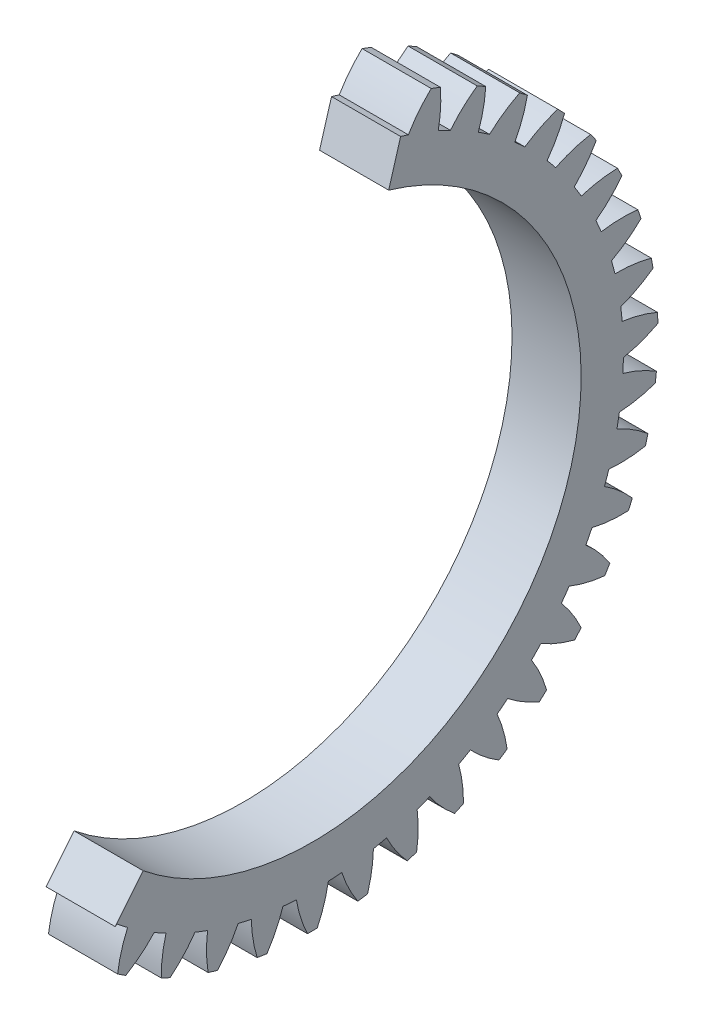
SolidWorks part; units mm, degrees
ref_plane "Plane1" through (0, 0, 0) normal (0, 0, 1) x (1, 0, 0)
ref_plane "Plane2" through (0, 0, 0) normal (0, 1, 0) x (1, 0, 0)
ref_plane "Plane3" through (0, 0, 0) normal (1, 0, 0) x (0, 0, -1)
sketch "HoldingSke" plane through (0, 0, 0) normal (0, 1, 0) x (1, 0, 0)
  line L0 (0, 0) -> (0.3657, -0.341)
  line L1 (-15, 0) -> (100, 0) construction
  line L2 (0, 0) -> (-2.1039, 2.3779)
  line L3 (0, 0) -> (-11.863, 4.5341)
  line L4 (0, 0) -> (6.316, 5.8897)
  line L5 (0, 0) -> (-46.8476, -17.4728)
  line L6 (0, 0) -> (-7.4607, -5.0337)
  line L7 (-2.1039, 2.3779) -> (8.6586, 51.2059)
  line L8 (-76.2, 54.61) -> (-75.2, 54.61)
  line L9 (-71.009, 38.7566) -> (-53.1078, 45.2721)
  line L10 (-76.2, 71.12) -> (104.1128, 71.12)
  line L11 (0, 0) -> (-9, 0)
  line L12 (-76.2, 101.6) -> (-76.133, 101.6)
  line L13 (24.9733, 27.94) -> (52.9518, 28.4284)
  line L14 (24.9733, 27.94) -> (24.9743, 27.94)
  line L15 (24.9733, 27.94) -> (100.4006, 29.5858)
  line L16 (-63.627, -2) -> (-12.827, -2)
  circle A0 centre (0, 0) radius 3
  circle A1 centre (0, 0) radius 37.5
  circle A2 centre (0, 0) radius 37.5
  circle A3 centre (0, 0) radius 3
  dimension "MHD" = 75
  dimension "Hub_dia" = 75
  dimension "Bore" = 6
  dimension "MBD" = 6
  dimension "Num_teeth" = 43
  dimension "Pitch" = 0.5
  dimension "Overall_len" = 50
  dimension "Show_teeth" = 43
  dimension "Thickness" = 9
  dimension "OAL" = 50.0001
  dimension "T_dim" = 1
  dimension "Ap" = 20
  dimension "H" = 19.05
  dimension "Pitch_radius" = 180.3128
  dimension "Width" = 9
  dimension "Backlash" = 0.067
  dimension "Addendum_fac" = 1
  dimension "Dedendum_fac" = 1.25
  dimension "Clearance_fac" = 0.25
  dimension "Dedendum_add" = 0.001
  dimension "Module" = 2
sketch "BasProSke" plane through (0, 0, 0) normal (0, 1, 0) x (1, 0, 0)
  line L0 (-10, 0) -> (60, 0) construction
  line L1 (0, 0) -> (0, 45)
  line L2 (0, 0) -> (9, 0)
  line L3 (9, 0) -> (9, 45)
  line L4 (9, 45) -> (0, 45)
  dimension "Thickness" = 9
  dimension "Diameter" = 90
revolve "Base-Revolve" add sketch "BasProSke" angle 360 about L0
sketch "TooCutSke" plane through (0, 0, 0) normal (1, 0, 0) x (0, 0, -1)
  line L1 (0, 0) -> (0, 107) construction
  line L2 (0, 0) -> (-1.6877, 42.9669) construction
  line L3 (0, 0) -> (-6.274, 85.7216) construction
  line L4 (-1.6877, 42.9669) -> (-3.137, 42.8608) construction
  arc A0 (0.8751, 40.4895) -> (-0.8751, 40.4895) centre (0, 0) ccw
  arc A1 (2.6611, 44.9467) -> (-2.6611, 44.9467) centre (0, 0) ccw
  circle A2 centre (0, 0) radius 43 construction
  circle A3 centre (0, 0) radius 40.4068 construction
  arc A4 (-0.8751, 40.4895) -> (-2.6611, 44.9467) centre (-17.5777, 36.3831) ccw
  arc A5 (2.6611, 44.9467) -> (0.8751, 40.4895) centre (17.5777, 36.3831) ccw
  dimension "Root_dia" = 80.998
  dimension "Overcut_dia" = 90.0508
  dimension "Pitch_dia" = 86
  dimension "Base_dia" = 80.8136
  dimension "Flank_rad" = 17.2
  dimension "Half_ang" = 4.186
  dimension "Half_CT" = 1.4532
extrude "ToothCut" cut sketch "TooCutSke" along normal through all
fillet "Breaks" [suppressed] radius 0.04
fillet "RootFillets" [suppressed] radius 0.501
pattern_circular "TeethCuts" count 43 every 8.372 about axis through (-10, 0, 0) along (1, 0, 0) of "ToothCut", "RootFillets", "Breaks"
sketch "HubNeaOneSke" plane through (0, 0, 0) normal (-1, 0, 0) x (0, 0, 1)
  circle A0 centre (0, 0) radius 37.5
  dimension "Diameter" = 75
extrude "HubNearOne" [suppressed] add sketch "HubNeaOneSke" along normal blind 41.0001
sketch "HubNeaBotSke" plane through (0, 0, 0) normal (-1, 0, 0) x (0, 0, 1)
  circle A0 centre (0, 0) radius 37.5
  dimension "Diameter" = 75
extrude "HubNearBoth" [suppressed] add sketch "HubNeaBotSke" along normal blind 20.5
ref_plane "FarPln" through (9, 0, 0) normal (1, 0, 0) x (0, 0, -1)
sketch "HubFarSke" plane through (9, 0, 0) normal (1, 0, 0) x (0, 0, -1)
  circle A0 centre (0, 0) radius 37.5
  dimension "Diameter" = 75
extrude "HubFar" [suppressed] add sketch "HubFarSke" along normal blind 20.5
sketch "BorSke" plane through (0, 0, 0) normal (1, 0, 0) x (0, 0, -1)
  circle A0 centre (0, 0) radius 3
  dimension "Diameter" = 6
extrude "Bore" cut sketch "BorSke" along normal mid plane 100.0001
sketch "KeySke" plane through (0, 0, 0) normal (1, 0, 0) x (0, 0, -1)
  line L0 (-1, 0) -> (-1, 4)
  line L1 (-1, 4) -> (1, 4)
  line L2 (1, 4) -> (1, 0)
  line L3 (0, 0) -> (0, 34) construction
  line L4 (-1, 0) -> (1, 0)
  dimension "Offset" = 4
  dimension "Width" = 2
extrude "Keyway" [suppressed] cut sketch "KeySke" along normal mid plane 100.0001
pattern_circular "Keyway2" [suppressed] count 2 every 90 about axis through (-10, 0, 0) along (1, 0, 0)
sketch "Szkic1" plane through (0, 0, 0) normal (1, 0, 0) x (0, 0, -1)
  line L1 (0, 0) -> (-31.4677, -38.8559) construction
  line L3 (14.1945, 47.9429) -> (0, 0) construction
  line L4 (-31.4677, -38.8559) -> (-22.0274, -27.1991)
  line L5 (14.1945, 47.9429) -> (9.9361, 33.56)
  line L6 (9.9361, 33.56) -> (14.1945, 47.9429)
  line L7 (-22.0274, -27.1991) -> (-31.4677, -38.8559)
  arc A0 (-31.4677, -38.8559) -> (14.1945, 47.9429) centre (0, 0) cw
  circle A1 centre (0, 0) radius 35 construction
  arc A3 (9.9361, 33.56) -> (-22.0274, -27.1991) centre (0, 0) cw
  arc A5 (-22.0274, -27.1991) -> (9.9361, 33.56) centre (0, 0) ccw
  dimension "D2" = 50
  dimension "D3" = 70
  dimension "D1" = 157.49
sketch "Szkic2" plane through (0, 0, 0) normal (1, 0, 0) x (0, 0, -1)
  line L0 (-31.4677, -38.8559) -> (-22.0274, -27.1991) construction
  line L1 (14.1945, 47.9429) -> (9.9361, 33.56) construction
  line L2 (-31.4677, -38.8559) -> (-22.0274, -27.1991)
  line L3 (14.1945, 47.9429) -> (9.9361, 33.56)
  arc A0 (-22.0274, -27.1991) -> (9.9361, 33.56) centre (0, 0) ccw construction
  arc A1 (14.1945, 47.9429) -> (-31.4677, -38.8559) centre (0, 0) ccw construction
  arc A2 (-22.0274, -27.1991) -> (9.9361, 33.56) centre (0, 0) ccw
  arc A3 (14.1945, 47.9429) -> (-31.4677, -38.8559) centre (0, 0) ccw
extrude "Wytnij-wyciągnięcie1" cut sketch "Szkic2" along normal through all
equation "' \"Module@HoldingSke\" = 6.35"
equation "' \"Num_teeth@HoldingSke\" = 12"
equation "' \"Ap@HoldingSke\" =  20"
equation "' \"Ap@HoldingSke\" = 20"
equation "' \"Width@HoldingSke\" = 0.5 * 25.4"
equation "' \"Hub_dia@HoldingSke\"= 1 * 25.4"
equation "' \"Hub_dia@HoldingSke\" = 1 * 25.4"
equation "' \"Overall_len@HoldingSke\" = 1.0 * 25.4"
equation "' \"Bore@HoldingSke\" = 0.75 * 25.4"
equation "' \"T_dim@HoldingSke\" = 0.1 * 25.4"
equation "' \"Width@KeySke\" = 0.25 * 25.4"
equation "' \"Show_teeth@HoldingSke\" = 13"
equation "' \"Backlash@HoldingSke\" = 0.009 * 25.4"
equation "' \"Addendum_fac@HoldingSke\" = 1.0"
equation "' \"Dedendum_fac@HoldingSke\" = 1.25"
equation "' \"Dedendum_add@HoldingSke\" = 0.00005 * 25.4"
equation "' \"Clearance_fac@HoldingSke\" = 0.25"
equation "\"Pitch@HoldingSke\" = 1 / \"Module@HoldingSke\""
equation "\"Overcut_dia@TooCutSke\" = (\"Num_teeth@HoldingSke\" + 2 * \"Addendum_fac@HoldingSke\") / \"Pitch@HoldingSke\" + 0.002 * 25.4"
equation "\"Pitch_dia@TooCutSke\" = \"Num_teeth@HoldingSke\" / \"Pitch@HoldingSke\""
equation "\"Base_dia@TooCutSke\" = \"Num_teeth@HoldingSke\" / \"Pitch@HoldingSke\" * cos((\"Ap@HoldingSke\"  * 3.14159265 / 180))"
equation "\"Root_dia@TooCutSke\" = (\"Num_teeth@HoldingSke\" + 2) / \"Pitch@HoldingSke\" - 2 * (\"Addendum_fac@HoldingSke\" + \"Dedendum_fac@HoldingSke\") / \"Pitch@HoldingSke\" - \"Dedendum_add@HoldingSke\" * 2"
equation "\"Half_ang@TooCutSke\" = 180 / \"Num_teeth@HoldingSke\""
equation "\"Half_CT@TooCutSke\" = \"Num_teeth@HoldingSke\" / \"Pitch@HoldingSke\" * sin((3.14159265 / 2 / \"Num_teeth@HoldingSke\")) / 2 - 7 * \"Backlash@HoldingSke\" / 4"
equation "\"Flank_rad@TooCutSke\" = \"Num_teeth@HoldingSke\" / \"Pitch@HoldingSke\" / 5"
equation "\"Radius@RootFillets\" = \"Clearance_fac@HoldingSke\" / \"Pitch@HoldingSke\" + \"Dedendum_add@HoldingSke\""
equation "\"Break_rad@Breaks\" = 0.02 / \"Pitch@HoldingSke\""
equation "\"Thickness@HoldingSke\" = \"Width@HoldingSke\""
equation "\"OAL@HoldingSke\" = \"Thickness@HoldingSke\""
equation "\"MHD@HoldingSke\" = (\"Num_teeth@HoldingSke\" + 2) / \"Pitch@HoldingSke\" - 2 * (\"Addendum_fac@HoldingSke\" + \"Dedendum_fac@HoldingSke\")  / \"Pitch@HoldingSke\" - \"Dedendum_add@HoldingSke\" * 2"
equation "\"MBD@HoldingSke\" = (\"Num_teeth@HoldingSke\" + 2) / \"Pitch@HoldingSke\" - 2 * (\"Addendum_fac@HoldingSke\" + \"Dedendum_fac@HoldingSke\")  / \"Pitch@HoldingSke\" - \"Dedendum_add@HoldingSke\" * 2 - 0.002 * 25.4"
equation "\"MHD@HoldingSke\" = ((sgn( \"MHD@HoldingSke\" - \"Hub_dia@HoldingSke\" )-1)*( \"MHD@HoldingSke\" - \"Hub_dia@HoldingSke\" ))/-2+ \"Hub_dia@HoldingSke\""
equation "\"MBD@HoldingSke\" = ((sgn( \"MBD@HoldingSke\" - \"Bore@HoldingSke\" )-1)*( \"MBD@HoldingSke\" - \"Bore@HoldingSke\" ))/-2+ \"Bore@HoldingSke\""
equation "\"OAL@HoldingSke\" = ((sgn( \"OAL@HoldingSke\" - \"Overall_len@HoldingSke\" )+1)*( \"OAL@HoldingSke\" - \"Overall_len@HoldingSke\" ))/2 + \"Overall_len@HoldingSke\" + 0.000002 * 25.4"
equation "\"Num_teeth@TeethCuts\" = int( \"Show_teeth@HoldingSke\" ) + 1"
equation "\"Num_teeth@TeethCuts\" = ((sgn( \"Num_teeth@TeethCuts\" - \"Num_teeth@HoldingSke\" )-1)*( \"Num_teeth@TeethCuts\" - \"Num_teeth@HoldingSke\" ))/-2+ \"Num_teeth@HoldingSke\""
equation "\"Num_teeth@TeethCuts\" = ((sgn( \"Num_teeth@TeethCuts\" - 2.0)+1)*( \"Num_teeth@TeethCuts\" - 2.0))/2 +2.0"
equation "\"Angle@TeethCuts\" = 360.0 / \"Num_teeth@HoldingSke\""
equation "\"Diameter@BasProSke\" = (\"Num_teeth@HoldingSke\" + 2 * \"Addendum_fac@HoldingSke\") / \"Pitch@HoldingSke\""
equation "\"Thickness@BasProSke\"  = \"Thickness@HoldingSke\""
equation "' \"Fillet_rad@BasProSke\" =  \"Thickness@HoldingSke\" * 0.05"
equation "' \"Fillet_rad@BasProSke\" = \"Thickness@HoldingSke\" * 0.05"
equation "\"MHD@HoldingSke\" = ((sgn( \"MHD@HoldingSke\" - \"Root_dia@TooCutSke\" )-1)*( \"MHD@HoldingSke\" - \"Root_dia@TooCutSke\" ))/-2+ \"Root_dia@TooCutSke\""
equation "\"Diameter@HubNeaOneSke\" = \"MHD@HoldingSke\""
equation "\"Length@HubNearOne\" = \"OAL@HoldingSke\" - \"Thickness@BasProSke\""
equation "\"Diameter@HubNeaBotSke\" = \"MHD@HoldingSke\""
equation "\"Length@HubNearBoth\" = ( \"OAL@HoldingSke\" - \"Thickness@BasProSke\" ) / 2.0"
equation "\"Thickness@FarPln\" = \"Thickness@BasProSke\""
equation "\"Diameter@HubFarSke\" = \"MHD@HoldingSke\""
equation "\"Length@HubFar\" = ( \"OAL@HoldingSke\" - \"Thickness@BasProSke\" ) / 2.0"
equation "\"Diameter@BorSke\" = \"MBD@HoldingSke\""
equation "\"D1@Bore\" = \"OAL@HoldingSke\" * 2.0"
equation "\"D1@Keyway\" = \"OAL@HoldingSke\" * 2.0"
equation "\"Offset@KeySke\" = \"T_dim@HoldingSke\" + \"MBD@HoldingSke\" / 2.0"
